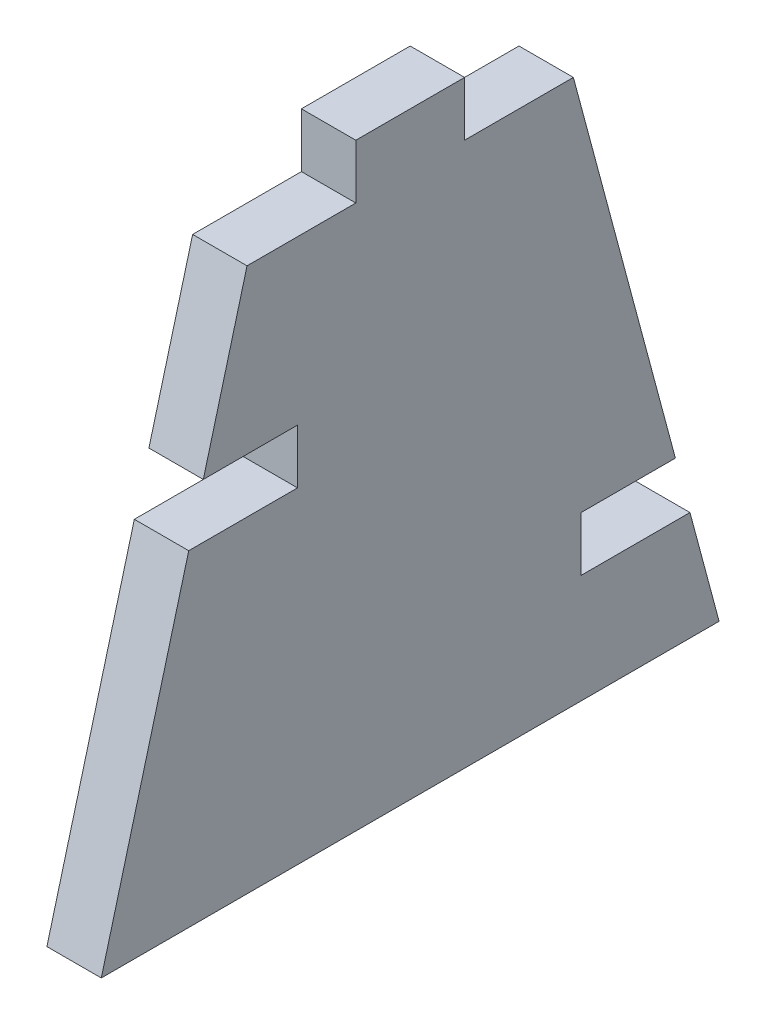
SolidWorks part; units mm, degrees
ref_plane "Front Plane" through (0, 0, 0) normal (0, 0, 1) x (1, 0, 0)
ref_plane "Top Plane" through (0, 0, 0) normal (0, 1, 0) x (1, 0, 0)
ref_plane "Right Plane" through (0, 0, 0) normal (1, 0, 0) x (0, 0, -1)
sketch "Sketch1" plane through (0, 0, 0) normal (1, 0, 0) x (0, 0, -1)
  line L0 (56.7949, 0) -> (-56.7949, 0)
  line L1 (-56.7949, 0) -> (-40.718, 60)
  line L2 (-30, 100) -> (-10, 100)
  line L3 (-10, 100) -> (-10, 110)
  line L4 (-10, 110) -> (10, 110)
  line L5 (0, 0) -> (0, 135.7256) construction
  line L6 (10, 100) -> (10, 110)
  line L7 (30, 100) -> (10, 100)
  line L8 (56.7949, 0) -> (51.4359, 20)
  line L9 (-38.0385, 70) -> (-20.718, 70)
  line L10 (-20.718, 70) -> (-20.718, 60)
  line L11 (-20.718, 60) -> (-40.718, 60)
  line L12 (48.7564, 30) -> (31.4359, 30)
  line L13 (31.4359, 30) -> (31.4359, 20)
  line L14 (31.4359, 20) -> (51.4359, 20)
  line L15 (48.7564, 30) -> (30, 100)
  line L16 (-38.0385, 70) -> (-30, 100)
  point P9 (0, 110)
  dimension "D1" = 100
  dimension "D2" = 20
  dimension "D3" = 75
  dimension "D4" = 30
  dimension "D5" = 10
  dimension "D6" = 60
  dimension "D7" = 10
  dimension "D8" = 20
  dimension "D9" = 20
  dimension "D10" = 10
extrude "Boss-Extrude1" add sketch "Sketch1" along normal blind 10
